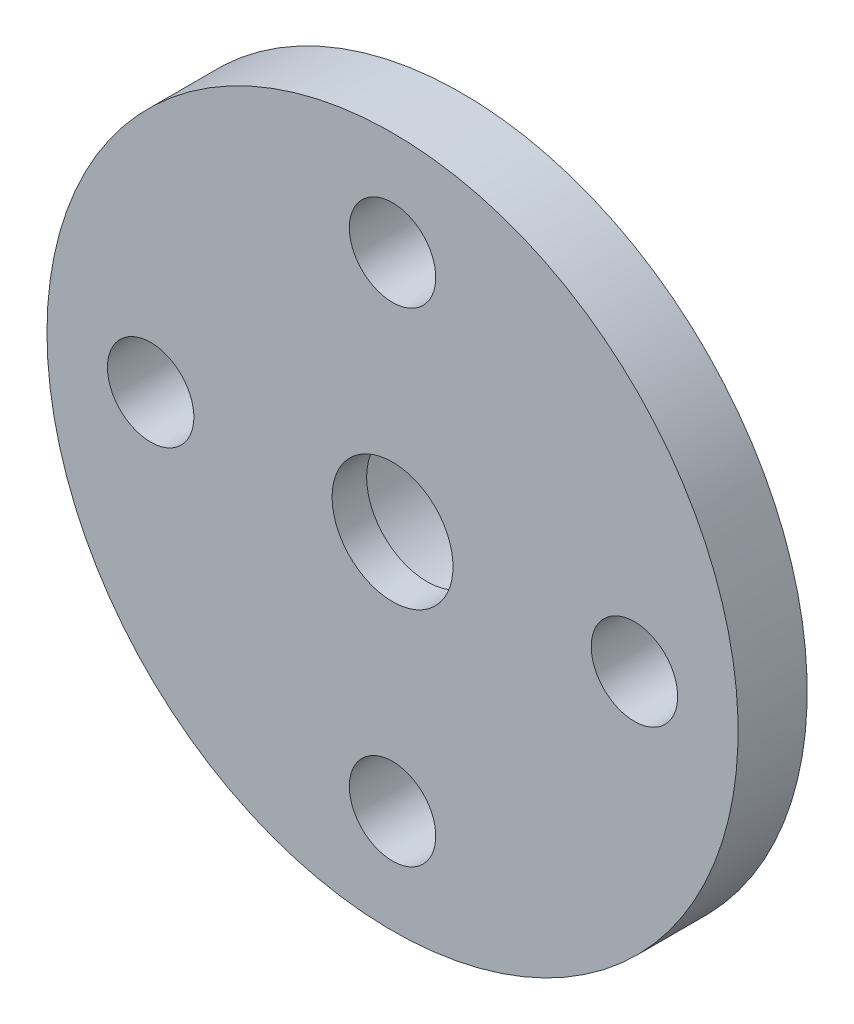
SolidWorks part; units mm, degrees
ref_plane "Front Plane" through (0, 0, 0) normal (0, 0, 1) x (1, 0, 0)
ref_plane "Top Plane" through (0, 0, 0) normal (0, 1, 0) x (1, 0, 0)
ref_plane "Right Plane" through (0, 0, 0) normal (1, 0, 0) x (0, 0, -1)
sketch "Sketch1" plane through (0, 0, 0) normal (0, 1, 0) x (1, 0, 0)
  line L0 (0, 13.3603) -> (0, -15.3086) construction
  line L1 (-1.75, 0) -> (-10, 0)
  line L2 (-1.75, 0) -> (-1.75, 1)
  line L3 (-1.75, 1) -> (-2.75, 1)
  line L4 (-2.75, 1) -> (-2.75, 4.5)
  line L5 (-2.75, 4.5) -> (-4.5, 4.5)
  line L6 (-4.5, 4.5) -> (-4.5, 2)
  line L7 (-4.5, 2) -> (-10, 2)
  line L8 (-10, 2) -> (-10, 0)
  dimension "D1" = 2
  dimension "D2" = 4.5
  dimension "D3" = 1
  dimension "D4" = 20
  dimension "D5" = 9
  dimension "D6" = 1
  dimension "D7" = 5.5
revolve "Revolve1" add sketch "Sketch1" angle 360 about L0
sketch "Sketch3" plane through (0, 0, 0) normal (0, 0, 1) x (1, 0, 0)
  circle A0 centre (0, 7) radius 1.5
  circle A1 centre (7, 0) radius 1.5
  circle A2 centre (0, -7) radius 1.5
  circle A3 centre (-7, 0) radius 1.5
  point P2 (7.3534, 0.4793)
  point P4 (0, 0)
  point P12 (0, 0)
  dimension "D1" = 7
  dimension "D2" = 3
  dimension "D3" = 4
hole_wizard "M3x0.5 Tapped Hole1" positions "Sketch4" profile "Sketch5" tap size "M3x0.5" standard "ANSI Metric" end condition through all
sketch "Sketch4" plane through (0, 0, -2) normal (0, 0, -1) x (-1, 0, 0)
  point P0 (0, 7)
  point P3 (7, 0)
  point P6 (0, -7)
  point P9 (-7, 0)
sketch "Sketch5" plane through (0, 7, -2) normal (1, 0, 0) x (0, 1, 0)
  line L0 (0, 0) -> (0, 2)
  line L1 (0, 2) -> (1.25, 2)
  line L2 (1.25, 2) -> (1.25, 0)
  line L5 (1.25, 0) -> (0, 0)
  line L11 (0, -6.35) -> (0, 107.95) construction
  dimension "Thru Tap Drill Dia." = 2.5
  dimension "Thru Tap Drill Depth" = 2
cosmetic thread "Hole Thread1" parameters "D2"=3
cosmetic thread "Hole Thread2" parameters "D2"=3
cosmetic thread "Hole Thread3" parameters "D2"=3
cosmetic thread "Hole Thread4" parameters "D2"=3
